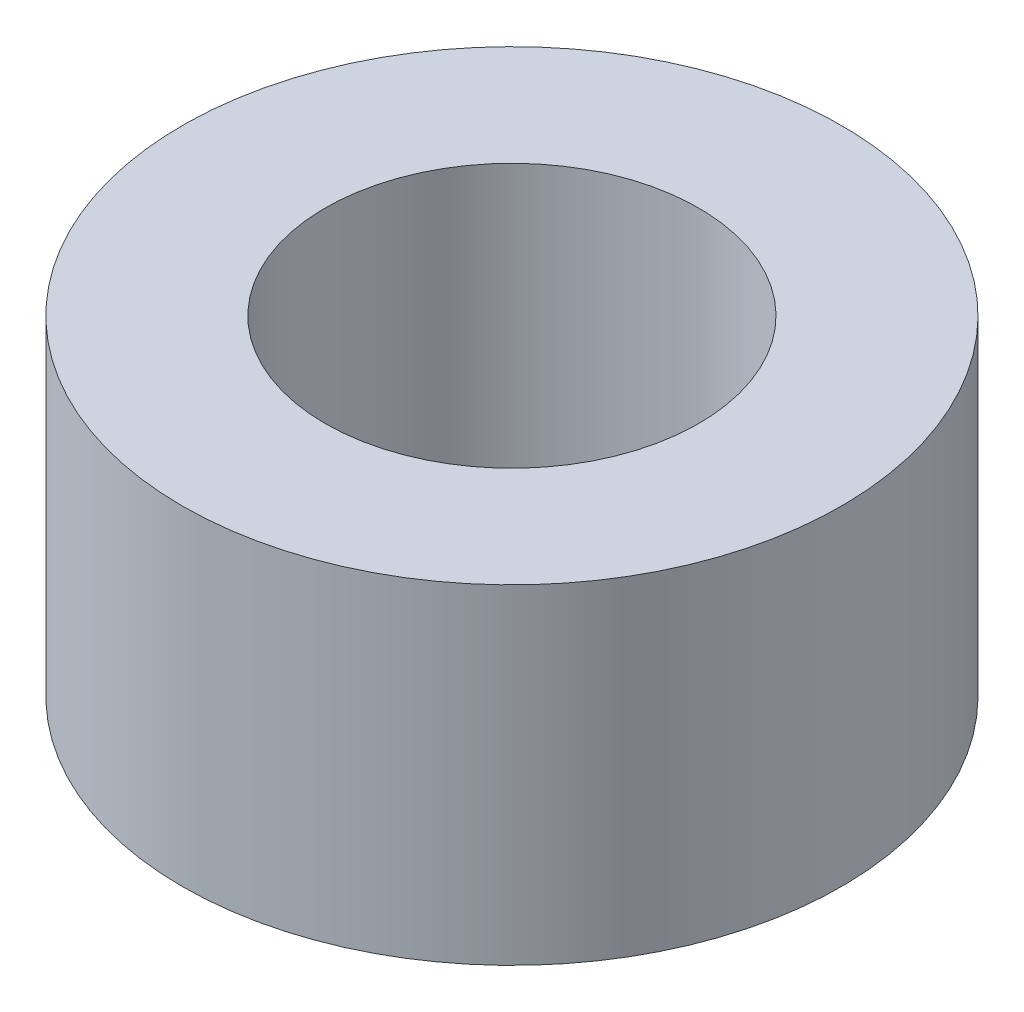
SolidWorks part; units mm, degrees
ref_plane "Front Plane" through (0, 0, 0) normal (0, 0, 1) x (1, 0, 0)
ref_plane "Top Plane" through (0, 0, 0) normal (0, 1, 0) x (1, 0, 0)
ref_plane "Right Plane" through (0, 0, 0) normal (1, 0, 0) x (0, 0, -1)
sketch "Sketch1" plane through (0, 0, 0) normal (0, 1, 0) x (1, 0, 0)
  circle A0 centre (0, 0) radius 3
  circle A1 centre (0, 0) radius 1.7
  dimension "D1" = 6
  dimension "D2" = 3.4
extrude "Boss-Extrude1" add sketch "Sketch1" along normal blind 3
